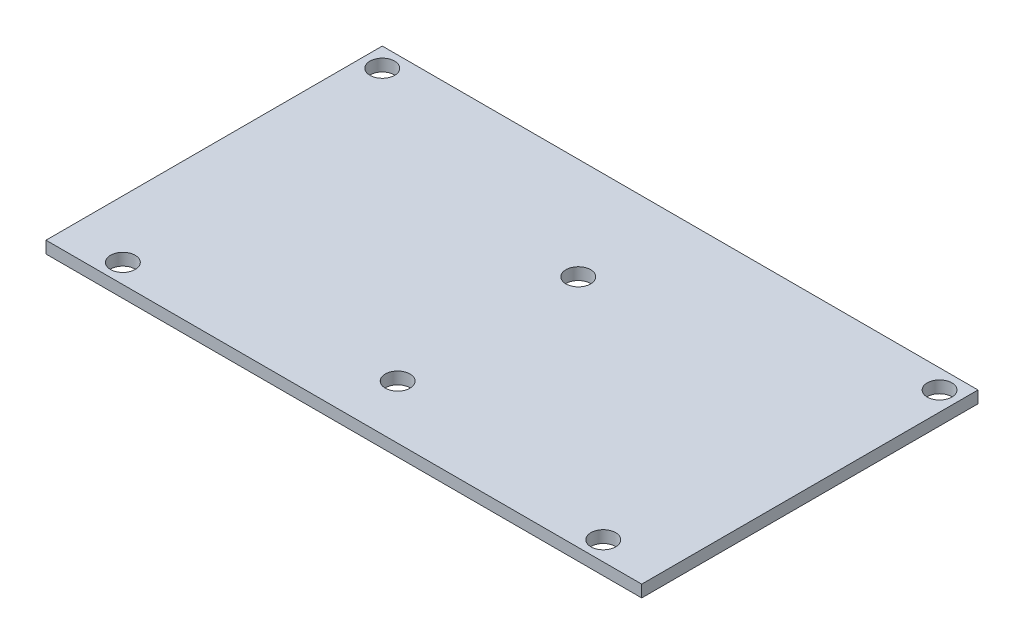
SolidWorks part; units mm, degrees
ref_plane "Front Plane" through (0, 0, 0) normal (0, 0, 1) x (1, 0, 0)
ref_plane "Top Plane" through (0, 0, 0) normal (0, 1, 0) x (1, 0, 0)
ref_plane "Right Plane" through (0, 0, 0) normal (1, 0, 0) x (0, 0, -1)
sketch "Sketch1" plane through (0, 0, 0) normal (0, 1, 0) x (1, 0, 0)
  line L1 (-39.37, 22.225) -> (39.37, 22.225)
  line L2 (-39.37, 22.225) -> (-39.37, -22.225)
  line L3 (-39.37, -22.225) -> (39.37, -22.225)
  line L4 (39.37, 22.225) -> (39.37, -22.225)
  line L5 (-39.37, 22.225) -> (39.37, -22.225) construction
  line L6 (-39.37, -22.225) -> (39.37, 22.225) construction
  point P0 (0, 0)
  dimension "D1" = 44.45
  dimension "D2" = 78.74
extrude "Boss-Extrude1" add sketch "Sketch1" along normal blind 1.5875
hole_wizard "#4 Clearance Hole1" positions "Sketch2" profile "Sketch3" hole size "#4" standard "ANSI Inch" end condition through all
sketch "Sketch2" plane through (0, 1.5875, 0) normal (0, 1, 0) x (1, 0, 0)
  point P0 (-36.83, 19.685)
  point P2 (36.83, 19.685)
  point P4 (31.75, -19.685)
  point P6 (-31.75, -19.685)
  dimension "D1" = 19.685
  dimension "D2" = 39.37
  dimension "D3" = 73.66
  dimension "D4" = 36.83
  dimension "D5" = 63.5
  dimension "D6" = 31.75
sketch "Sketch3" plane through (-36.83, 1.5875, -19.685) normal (1, 0, 0) x (0, 0, 1)
  line L0 (0, 0) -> (0, 1.5875)
  line L1 (0, 1.5875) -> (1.6319, 1.5875)
  line L2 (1.6319, 1.5875) -> (1.6319, 0)
  line L5 (1.6319, 0) -> (0, 0)
  line L11 (0, -6.35) -> (0, 107.95) construction
  dimension "Thru Hole Dia." = 3.2639
  dimension "Thru Hole Depth" = 1.5875
hole_wizard "#4 Clearance Hole2" positions "Sketch4" profile "Sketch6" hole size "#4" standard "ANSI Inch" end condition up to next
sketch "Sketch4" plane through (0, 1.5875, 0) normal (0, 1, 0) x (1, 0, 0)
  line L0 (39.37, -22.225) -> (39.37, 22.225) construction
  point P0 (0, 8.763)
  point P3 (0, -15.113)
  dimension "D1" = 23.876
  dimension "D2" = 8.763
  dimension "D3" = 39.37
sketch "Sketch6" plane through (0, 1.5875, -8.763) normal (1, 0, 0) x (0, 0, 1)
  line L0 (0, 0) -> (0, 1.5875)
  line L1 (0, 1.5875) -> (1.6319, 1.5875)
  line L2 (1.6319, 1.5875) -> (1.6319, 0)
  line L5 (1.6319, 0) -> (0, 0)
  line L11 (0, -6.35) -> (0, 107.95) construction
  dimension "Thru Hole Dia." = 3.2639
  dimension "Thru Hole Depth" = 1.5875
